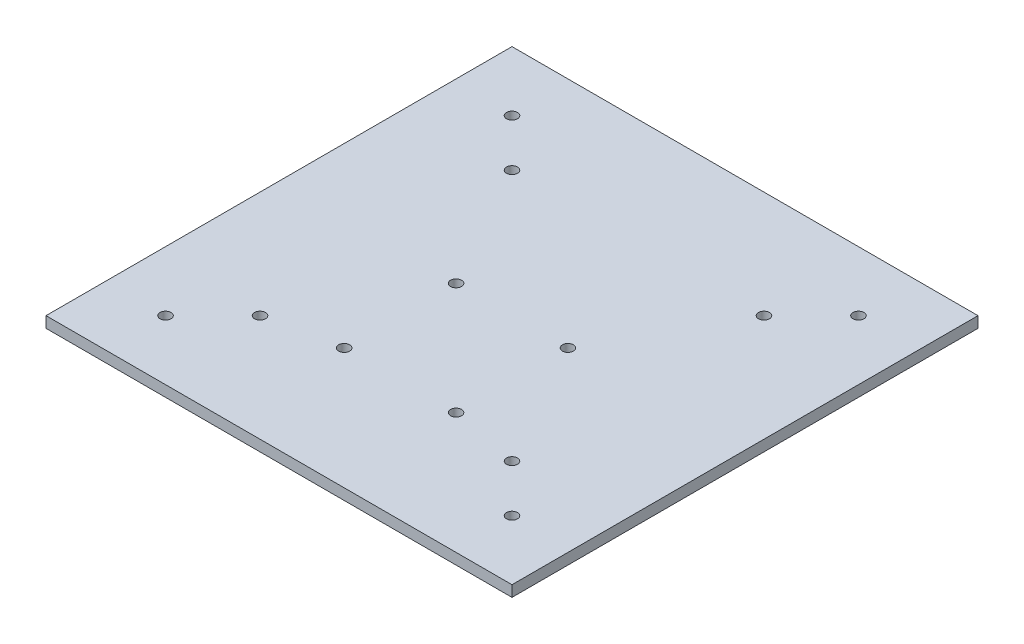
SolidWorks part; units mm, degrees
ref_plane "Front Plane" through (0, 0, 0) normal (0, 0, 1) x (1, 0, 0)
ref_plane "Top Plane" through (0, 0, 0) normal (0, 1, 0) x (1, 0, 0)
ref_plane "Right Plane" through (0, 0, 0) normal (1, 0, 0) x (0, 0, -1)
sketch "Sketch2" plane through (0, 0, 0) normal (0, 1, 0) x (1, 0, 0)
  line L1 (63.5, 63.5) -> (-63.5, 63.5)
  line L2 (63.5, 63.5) -> (63.5, -63.5)
  line L3 (63.5, -63.5) -> (-63.5, -63.5)
  line L4 (-63.5, 63.5) -> (-63.5, -63.5)
  line L5 (63.5, 63.5) -> (-63.5, -63.5) construction
  line L6 (63.5, -63.5) -> (-63.5, 63.5) construction
  point P0 (0, 0)
  dimension "D1" = 127
  dimension "D2" = 127
extrude "Boss-Extrude1" add sketch "Sketch2" along normal blind 3
sketch "Sketch3" plane through (0, 3, 0) normal (0, 1, 0) x (1, 0, 0)
  line L0 (-63.5, 63.5) -> (63.5, -63.5) construction
  line L1 (0, 63.5) -> (0, -63.5) construction
  line L2 (63.5, 63.5) -> (-63.5, 63.5) construction
  line L3 (-63.5, -63.5) -> (63.5, -63.5) construction
  circle A0 centre (-47.2147, 47.2147) radius 1.5
  circle A1 centre (-34.3371, 34.3371) radius 1.5
  circle A2 centre (47.2147, 47.2147) radius 1.5
  circle A3 centre (34.3371, 34.3371) radius 1.5
  circle A4 centre (47.2147, -47.2147) radius 1.5
  circle A5 centre (34.3371, -34.3371) radius 1.5
  circle A6 centre (-47.2147, -47.2147) radius 1.5
  circle A7 centre (-34.3371, -34.3371) radius 1.5
  point P28 (0, 0)
  dimension "D1" = 4
extrude "Cut-Extrude1" cut sketch "Sketch3" against normal through all both and the other way through all
sketch "Sketch4" plane through (0, 3, 0) normal (0, 1, 0) x (1, 0, 0)
  line L0 (0, 129.7192) -> (0, -138.5455) construction
  line L5 (15.25, -30.5) -> (-15.25, 0) construction
  line L6 (15.25, 0) -> (-15.25, -30.5) construction
  line L7 (0, 0) -> (-200.7917, 0) construction
  circle A0 centre (-15.25, 0) radius 1.5
  circle A1 centre (15.25, 0) radius 1.5
  circle A2 centre (-15.25, -30.5) radius 1.5
  circle A3 centre (15.25, -30.5) radius 1.5
  point P0 (0, -15.25)
  dimension "D1" = 30.5
  dimension "D2" = 30.5
extrude "Cut-Extrude2" cut sketch "Sketch4" against normal blind 10
